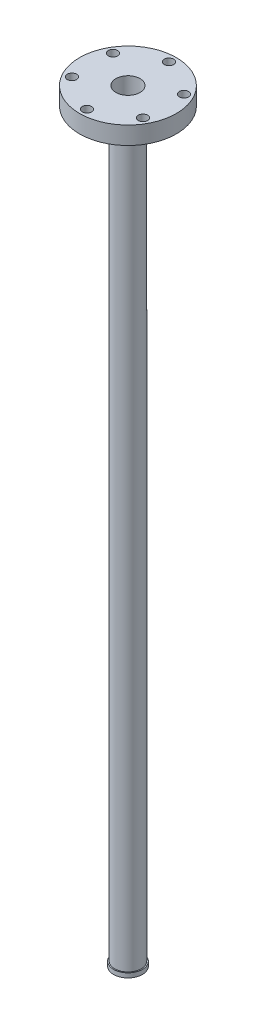
SolidWorks part; units mm, degrees
ref_plane "Front Plane" through (0, 0, 0) normal (0, 0, 1) x (1, 0, 0)
ref_plane "Top Plane" through (0, 0, 0) normal (0, 1, 0) x (1, 0, 0)
ref_plane "Right Plane" through (0, 0, 0) normal (1, 0, 0) x (0, 0, -1)
sketch "Sketch1" plane through (0, 0, 0) normal (0, 1, 0) x (1, 0, 0)
  circle A0 centre (0, 0) radius 9.525
  circle A1 centre (0, 0) radius 8.636
  dimension "D1" = 19.05
  dimension "D2" = 17.272
extrude "Extrude1" add sketch "Sketch1" along normal blind 546.1
sketch "Sketch2" plane through (0, 546.1, 0) normal (0, 1, 0) x (1, 0, 0)
  circle A0 centre (0, 0) radius 8.636
  circle A1 centre (0, 0) radius 34.671
  dimension "D1" = 69.342
extrude "Extrude2" add sketch "Sketch2" against normal blind 12.7
sketch "Sketch3" plane through (0, 546.1, 0) normal (0, 1, 0) x (1, 0, 0)
  line L0 (0, 0) -> (0, 29.3624) construction
  circle A0 centre (0, 29.3624) radius 3.3655
  dimension "D1" = 6.731
  dimension "D2" = 29.3624
extrude "Extrude3" cut sketch "Sketch3" against normal through all
pattern_circular "CirPattern1" count 6 over 360 about axis through (0, 0, 0) along (0, 1, 0) of "Extrude3"
sketch "Sketch4" plane through (0, 0, 0) normal (0, -1, 0) x (1, 0, 0)
  circle A0 centre (0, 0) radius 8.636
  circle A1 centre (0, 0) radius 10.3187
  dimension "D1" = 20.6375
extrude "Extrude4" add sketch "Sketch4" against normal blind 3.175
